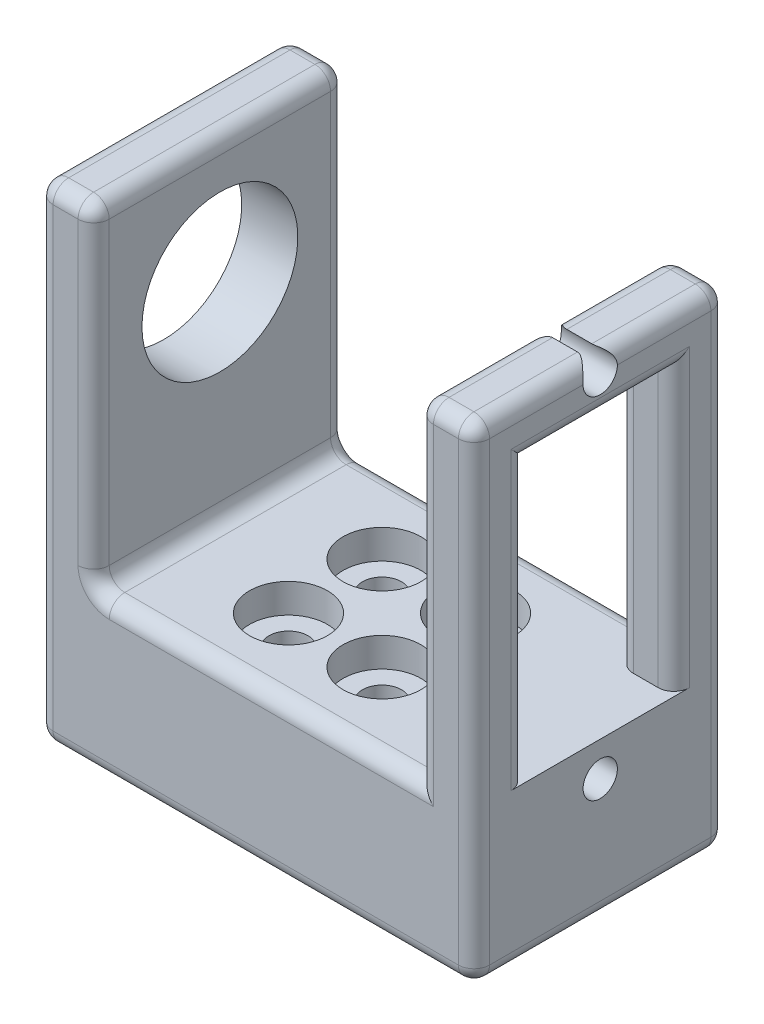
SolidWorks part; units mm, degrees
ref_plane "Front Plane" through (0, 0, 0) normal (0, 0, 1) x (1, 0, 0)
ref_plane "Top Plane" through (0, 0, 0) normal (0, 1, 0) x (1, 0, 0)
ref_plane "Right Plane" through (0, 0, 0) normal (1, 0, 0) x (0, 0, -1)
sketch "Sketch1" plane through (0, 0, 0) normal (0, 1, 0) x (1, 0, 0)
  line L1 (-17.78, 0) -> (17.78, 0)
  line L2 (-17.78, 0) -> (-17.78, 20.574)
  line L3 (-17.78, 20.574) -> (17.78, 20.574)
  line L4 (17.78, 0) -> (17.78, 20.574)
  point P4 (0, 0)
  dimension "D1" = 20.574
  dimension "D2" = 35.56
extrude "Boss-Extrude1" add sketch "Sketch1" along normal blind 12.7
sketch "Sketch2" plane through (0, 0, 0) normal (0, -1, 0) x (1, 0, 0)
  line L0 (17.78, 0) -> (17.78, -20.574) construction
  line L1 (-13.208, -4.572) -> (13.208, -4.572)
  line L2 (-13.208, -4.572) -> (-13.208, -16.002)
  line L3 (-13.208, -16.002) -> (13.208, -16.002)
  line L4 (13.208, -4.572) -> (13.208, -16.002)
  line L5 (-17.78, -20.574) -> (-17.78, 0) construction
  line L6 (-17.78, 0) -> (17.78, 0) construction
  line L7 (17.78, -20.574) -> (-17.78, -20.574) construction
  dimension "D1" = 4.572
  dimension "D2" = 4.572
  dimension "D3" = 4.572
  dimension "D4" = 4.572
extrude "Cut-Extrude1" cut sketch "Sketch2" against normal blind 6.35
hole_wizard "CBORE for 5/16 Truss Head Screw1" positions "3DSketch1" profile "Sketch4" counterbore size "5/16" standard "ANSI Inch"
sketch3d "3DSketch1"
  line L6 (-3.81, 12.7, -6.477) -> (-3.81, 12.7, -14.097) construction
  line L7 (-3.81, 12.7, -6.477) -> (3.81, 12.7, -6.477) construction
  line L8 (-3.81, 12.7, -14.097) -> (3.81, 12.7, -14.097) construction
  line L9 (3.81, 12.7, -6.477) -> (3.81, 12.7, -14.097) construction
  line L12 (13.208, 6.35, -16.002) -> (-13.208, 6.35, -4.572) construction
  line L14 (-13.208, 6.35, -16.002) -> (13.208, 6.35, -4.572) construction
  line L16 (-3.81, 12.7, -14.097) -> (3.81, 12.7, -6.477) construction
  line L18 (3.81, 12.7, -14.097) -> (-3.81, 12.7, -6.477) construction
  line L21 (0, 6.35, -10.287) -> (0, 12.7, -10.287)
  point P0 (-3.81, 12.7, -14.097)
  point P6 (3.81, 12.7, -14.097)
  point P19 (-3.81, 12.7, -6.477)
  point P21 (3.81, 12.7, -6.477)
  point P625 (0, 6.35, -10.287)
  point P630 (-4.8062, 124.3106, 0)
  dimension "D1" = 7.62
  dimension "D2" = 7.62
sketch "Sketch4" plane through (-3.81, 12.7, -14.097) normal (1, 0, 0) x (0, 0, 1)
  line L0 (0, 0) -> (0, 8.8914)
  line L1 (0, 8.8914) -> (1.5875, 7.9375)
  line L2 (1.5875, 7.9375) -> (1.5875, 2.3813)
  line L3 (1.5875, 2.3813) -> (3.175, 2.3813)
  line L4 (3.175, 2.3813) -> (3.175, 0)
  line L5 (3.175, 0) -> (0, 0)
  line L10 (0, 8.8914) -> (-1.5875, 7.9375) construction
  line L11 (0, -6.35) -> (0, 107.95) construction
  dimension "Hole Dia." = 3.175
  dimension "Hole Depth" = 7.9375
  dimension "C'Bore Dia." = 6.35
  dimension "C'Bore Depth" = 2.3812
  dimension "Drill Angle" = 118
sketch "Sketch5" plane through (0, 12.7, 0) normal (0, 1, 0) x (1, 0, 0)
  line L0 (-17.78, 0) -> (17.78, 0) construction
  line L1 (-17.78, 20.574) -> (-13.208, 20.574)
  line L2 (-17.78, 20.574) -> (-17.78, 0)
  line L3 (-17.78, 0) -> (-13.208, 0)
  line L4 (-13.208, 20.574) -> (-13.208, 0)
  line L5 (17.78, 20.574) -> (-17.78, 20.574) construction
  line L6 (17.78, 0) -> (13.208, 0)
  line L7 (17.78, 0) -> (17.78, 20.574)
  line L8 (17.78, 20.574) -> (13.208, 20.574)
  line L9 (13.208, 0) -> (13.208, 20.574)
  dimension "D1" = 4.572
  dimension "D2" = 4.572
extrude "Boss-Extrude2" add sketch "Sketch5" along normal blind 26.9748
sketch "Sketch7" plane through (17.78, 0, 0) normal (1, 0, 0) x (0, 0, -1)
  line L0 (16.2814, 24.1046) -> (20.574, 24.1046) construction
  line L1 (16.2814, 35.5092) -> (4.2926, 35.5092)
  line L2 (16.2814, 35.5092) -> (16.2814, 12.7)
  line L3 (16.2814, 12.7) -> (4.2926, 12.7)
  line L4 (4.2926, 35.5092) -> (4.2926, 12.7)
  line L5 (20.574, 39.6748) -> (20.574, 0) construction
  line L6 (4.2926, 24.1046) -> (0, 24.1046) construction
  line L7 (0, 39.6748) -> (0, 0) construction
  line L8 (20.574, 12.7) -> (0, 12.7) construction
  dimension "D1" = 11.9888
  dimension "D2" = 22.8092
  dimension "D3" = 22.8092
extrude "Cut-Extrude2" cut sketch "Sketch7" against normal up to next
hole_wizard "#60 (0.04) Diameter Hole1" positions "Sketch9" profile "Sketch8" hole size "#60" standard "ANSI Inch"
sketch "Sketch9" plane through (17.78, 0, 0) normal (1, 0, 0) x (0, 0, -1)
  line L0 (20.574, 39.6748) -> (20.574, 0) construction
  line L1 (10.287, 38.4048) -> (20.574, 38.4048) construction
  line L3 (10.287, 38.4048) -> (0, 38.4048) construction
  line L4 (0, 39.6748) -> (0, 0) construction
  line L6 (10.2868, 9.906) -> (0, 9.8071) construction
  line L8 (10.2868, 9.906) -> (20.574, 9.906) construction
  line L9 (16.2814, 35.5092) -> (4.2926, 35.5092) construction
  line L10 (4.2926, 12.7) -> (16.2814, 12.7) construction
  point P0 (10.287, 38.4048)
  point P2 (10.2868, 9.906)
  dimension "D1" = 2.8956
  dimension "D2" = 2.794
sketch "Sketch8" plane through (17.78, 38.4048, -10.287) normal (0, 1, 0) x (0, 0, -1)
  line L0 (0, 0) -> (0, 5.9194)
  line L1 (0, 5.9194) -> (1.397, 5.08)
  line L2 (1.397, 5.08) -> (1.397, 0)
  line L5 (1.397, 0) -> (0, 0)
  line L10 (0, 5.9194) -> (-1.397, 5.08) construction
  line L11 (0, -6.35) -> (0, 107.95) construction
  dimension "Hole Dia." = 2.794
  dimension "Hole Depth" = 5.08
  dimension "Drill Angle" = 118
sketch "Sketch10" plane through (-17.78, 0, 0) normal (-1, 0, 0) x (0, 0, 1)
  line L0 (0, 12.7) -> (-20.574, 12.7) construction
  line L1 (-3.937, 29.464) -> (0, 29.464) construction
  line L2 (0, 39.6748) -> (0, 0) construction
  line L3 (-16.637, 29.464) -> (-20.574, 29.464) construction
  line L4 (-20.574, 39.6748) -> (-20.574, 0) construction
  circle A0 centre (-10.287, 29.464) radius 6.35
  dimension "D1" = 12.7
  dimension "D2" = 16.764
extrude "Cut-Extrude3" cut sketch "Sketch10" against normal up to next
fillet "Fillet1" radius 1.27 35 edges at (17.78, 39.6748, -15.7215) (17.78, 39.6748, -4.8525) (13.208, 39.6748, -15.7215) (13.208, 39.6748, -4.8525) (-13.208, 39.6748, -10.287) (13.208, 26.1874, -20.574) (13.208, 26.1874, 0) (15.494, 39.6748, -20.574) (15.494, 39.6748, 0) (-15.494, 39.6748, -20.574) (-15.494, 39.6748, 0) (13.208, 35.5092, -10.287) (17.78, 35.5092, -10.287) (13.208, 24.1046, -4.2926) (17.78, 24.1046, -4.2926) (13.208, 24.1046, -16.2814) (17.78, 24.1046, -16.2814) (13.208, 0, -10.287) (0, 0, -4.572) (-13.208, 0, -10.287) (0, 0, -16.002) (-17.78, 0, -10.287) (0, 0, 0) (0, 0, -20.574) (17.78, 0, -10.287) (17.78, 19.8374, -20.574) (17.78, 19.8374, 0) (-17.78, 39.6748, -10.287) (-17.78, 19.8374, -20.574) (-17.78, 19.8374, 0)
